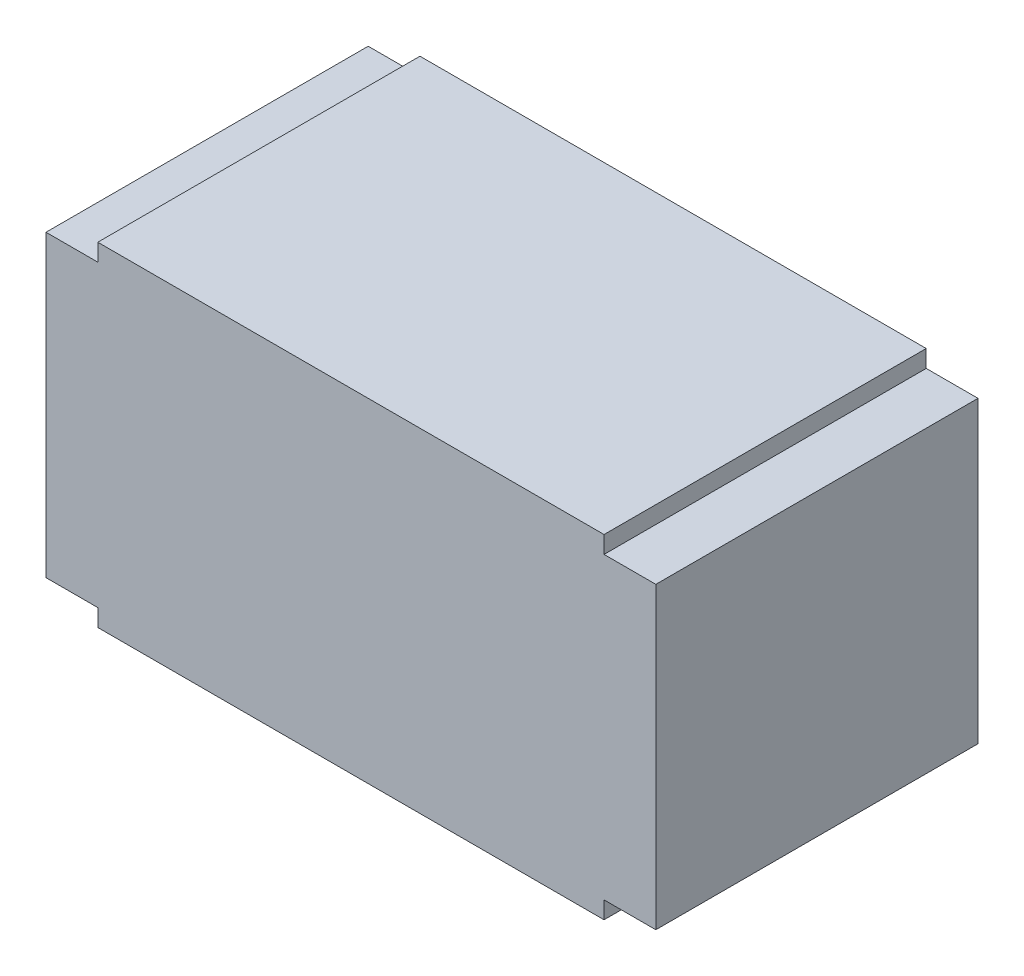
SolidWorks part; units mm, degrees
ref_plane "前视基准面" through (0, 0, 0) normal (0, 0, 1) x (1, 0, 0)
ref_plane "上视基准面" through (0, 0, 0) normal (0, 1, 0) x (1, 0, 0)
ref_plane "右视基准面" through (0, 0, 0) normal (1, 0, 0) x (0, 0, -1)
sketch "草图1" plane through (0, 0, 0) normal (0, 0, 1) x (1, 0, 0)
  line L0 (-1.1, -0.725) -> (-1.1, -0.66)
  line L1 (-1.1, -0.66) -> (-1.1, -0.65)
  line L2 (-1.1, -0.65) -> (-1.325, -0.65)
  line L3 (-1.325, -0.65) -> (-1.325, 0.65)
  line L4 (-1.325, 0.65) -> (-1.1, 0.65)
  line L5 (-1.1, 0.65) -> (-1.1, 0.725)
  line L6 (-1.1, 0.725) -> (1.1, 0.725)
  line L7 (1.1, 0.725) -> (1.1, 0.65)
  line L8 (1.1, 0.65) -> (1.325, 0.65)
  line L9 (1.325, 0.65) -> (1.325, -0.65)
  line L10 (1.325, -0.65) -> (1.1, -0.65)
  line L11 (1.1, -0.65) -> (1.1, -0.725)
  line L12 (1.1, -0.725) -> (-1.1, -0.725)
extrude "Component_Outline" add sketch "草图1" along normal blind 1.4 separate body
sketch3d "3D草图1"
  line L0 (0, 0, 0) -> (1, 0, 0)
  line L1 (0, 0, 0) -> (0, 1, 0)
  line L2 (0, 0, 0) -> (0, 0, 1)
  point P0 (0, 0, 0)
